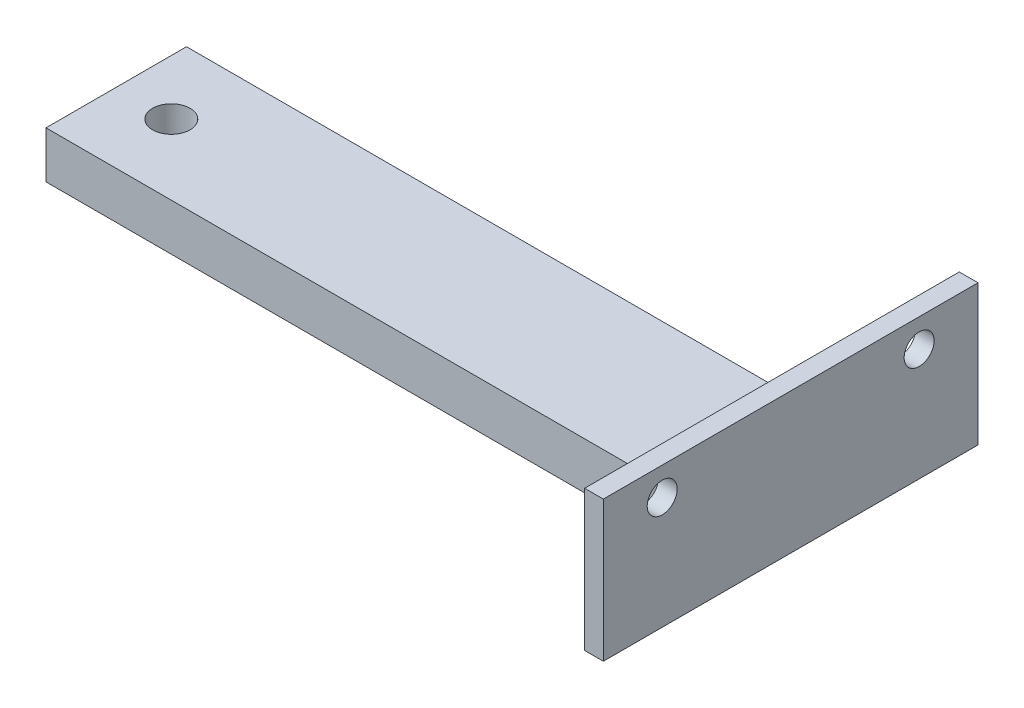
SolidWorks part; units mm, degrees
ref_plane "前视基准面" through (0, 0, 0) normal (0, 0, 1) x (1, 0, 0)
ref_plane "上视基准面" through (0, 0, 0) normal (0, 1, 0) x (1, 0, 0)
ref_plane "右视基准面" through (0, 0, 0) normal (1, 0, 0) x (0, 0, -1)
other "Configuration Table"
sketch "草图3" plane through (0, 0, 0) normal (0, 0, 1) x (1, 0, 0)
  line L0 (0, 0) -> (70, 0)
  line L1 (70, 0) -> (70, 5)
  line L2 (70, 5) -> (0, 5)
  line L3 (0, 5) -> (0, 0)
  point P3 (0, 0)
  dimension "D1" = 5
  dimension "D2" = 70
extrude "凸台-拉伸3" add sketch "草图3" along normal blind 15 contours L0 L1 L2 L3
sketch "草图4" plane through (0, 0, 0) normal (0, 1, 0) x (1, 0, 0)
  circle A0 centre (5.8788, -7.5) radius 2
  dimension "D1" = 4
extrude "切除-拉伸1" cut sketch "草图4" along normal up to next
sketch "草图7" plane through (70, 0, 0) normal (1, 0, 0) x (0, 0, -1)
  line L0 (-27.4941, 12.9217) -> (-7.4941, 12.9217)
  line L1 (-27.4941, 12.9217) -> (12.5059, 12.9217)
  line L2 (-27.4941, 12.9217) -> (-27.4941, -2.0783)
  line L3 (-27.4941, -2.0783) -> (12.5059, -2.0783)
  line L4 (12.5059, 12.9217) -> (12.5059, -2.0783)
  point P4 (0, 0)
  dimension "D1" = 15
  dimension "D2" = 40
extrude "凸台-拉伸5" add sketch "草图7" along normal blind 2 from offset 0 contours L2 L3 L4 L1
sketch "草图9" plane through (72, 0, 0) normal (1, 0, 0) x (0, 0, -1)
  line L0 (-27.4941, 12.9217) -> (12.5059, 12.9217) construction
  circle A0 centre (-21.2101, 9.9233) radius 1.6
  circle A1 centre (6.2219, 9.9233) radius 1.6
  dimension "D3" = 3.2
  dimension "D4" = 3.2
  dimension "D1" = 2.9984
  dimension "D2" = 2.9984
extrude "切除-拉伸2" cut sketch "草图9" against normal up to next
